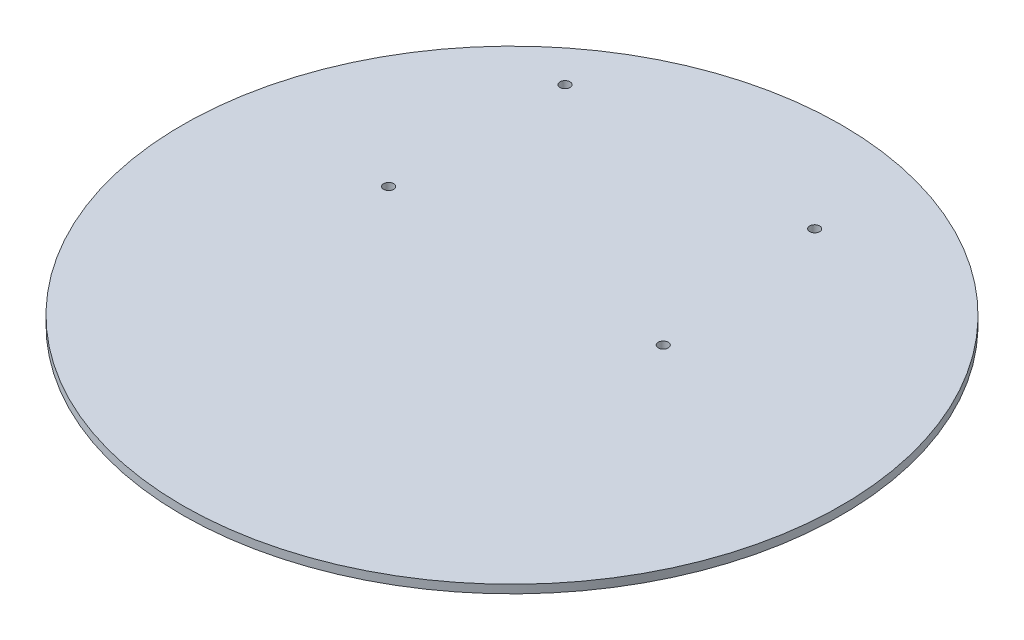
SolidWorks part; units mm, degrees
ref_plane "Front Plane" through (0, 0, 0) normal (0, 0, 1) x (1, 0, 0)
ref_plane "Top Plane" through (0, 0, 0) normal (0, 1, 0) x (1, 0, 0)
ref_plane "Right Plane" through (0, 0, 0) normal (1, 0, 0) x (0, 0, -1)
sketch "Sketch1" plane through (0, 0, 0) normal (0, 1, 0) x (1, 0, 0)
  circle A0 centre (0, 0) radius 99
extrude "Boss-Extrude1" add sketch "Sketch1" along normal blind 2.5 contours A0
sketch "Sketch2" plane through (0, 2.5, 0) normal (0, 1, 0) x (1, 0, 0)
  circle A0 centre (0, 0) radius 96.5
extrude "Cut-Extrude1" cut sketch "Sketch2" against normal blind 2.5 contours A0
sketch "Sketch3" plane through (0, 2.5, 0) normal (0, 1, 0) x (1, 0, 0)
  line L0 (0, 96.5) -> (0, 67.9417)
  line L1 (-52.0115, 67.9417) -> (22.9885, 67.9417)
  line L2 (-52.0115, 67.9417) -> (-52.0115, 14.9417)
  line L3 (-52.0115, 14.9417) -> (30.4885, 14.9417)
  line L4 (-52.0115, 20.8318) -> (37.9885, 20.8318)
  circle A0 centre (0, 0) radius 96.5 construction
  circle A1 centre (-52.0115, 14.9417) radius 1.5
  circle A2 centre (-52.0115, 67.9417) radius 1.5
  circle A3 centre (22.9885, 67.9417) radius 1.5
  circle A4 centre (30.4885, 14.9417) radius 1.5
  circle A5 centre (0, 0) radius 96.5
extrude "Boss-Extrude3" add sketch "Sketch3" against normal blind 2.5
sketch "Sketch4" plane through (0, 2.5, 0) normal (0, 1, 0) x (1, 0, 0)
  line L0 (-56.1886, -59.3834) -> (25.8114, -59.3834)
  line L1 (25.8114, -59.3834) -> (25.8114, -4.3834)
  line L4 (25.8114, -4.3834) -> (-56.1886, -4.3834)
  line L5 (-56.1886, -4.3834) -> (-56.1886, -59.3834)
  line L6 (-49.665, 43.9498) -> (21.5247, 43.9498) construction
  line L11 (-49.665, 63.028) -> (21.5247, 63.028)
  line L12 (-49.665, 24.8717) -> (21.5247, 24.8717)
  line L13 (63.5124, 24.8717) -> (63.5124, -39.8251) construction
  line L14 (82.8047, 24.8717) -> (82.8047, -39.8251)
  line L15 (44.2201, 24.8717) -> (44.2201, -39.8251)
  arc A0 (-49.665, 63.028) -> (-49.665, 24.8717) centre (-49.665, 43.9498) ccw
  arc A1 (21.5247, 24.8717) -> (21.5247, 63.028) centre (21.5247, 43.9498) ccw
  arc A2 (82.8047, 24.8717) -> (44.2201, 24.8717) centre (63.5124, 24.8717) ccw
  arc A3 (44.2201, -39.8251) -> (82.8047, -39.8251) centre (63.5124, -39.8251) ccw
  point P6 (-14.0701, 43.9498)
  point P11 (63.5124, -7.4767)
